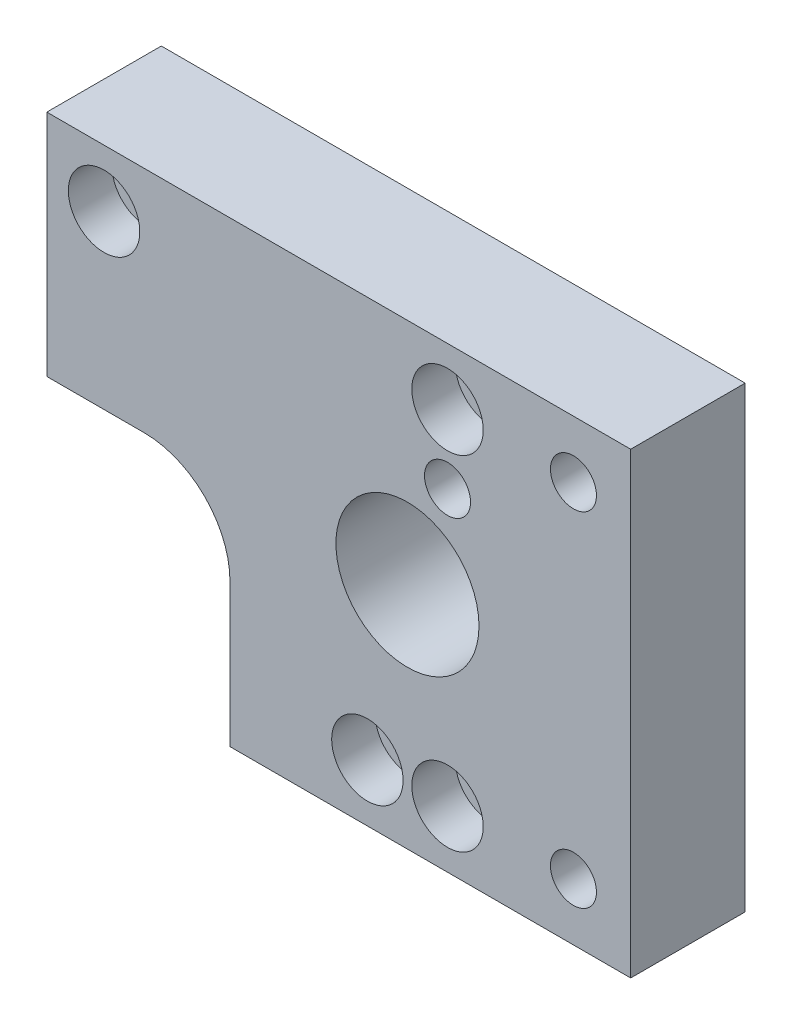
SolidWorks part; units mm, degrees
material "1060 Alloy"
ref_plane "Front Plane" through (0, 0, 0) normal (0, 0, 1) x (1, 0, 0)
ref_plane "Top Plane" through (0, 0, 0) normal (0, 1, 0) x (1, 0, 0)
ref_plane "Right Plane" through (0, 0, 0) normal (1, 0, 0) x (0, 0, -1)
sketch "Sketch1" plane through (0, 0, 0) normal (0, 0, 1) x (1, 0, 0)
  line L0 (0, 25.4) -> (0, 0) construction
  line L1 (-25.4, -25.4) -> (39.37, -25.4)
  line L2 (-25.4, -25.4) -> (-25.4, 25.4)
  line L3 (-25.4, 25.4) -> (39.37, 25.4)
  line L4 (39.37, -25.4) -> (39.37, 25.4)
  line L7 (39.37, 0) -> (-25.4, 0) construction
  circle A0 centre (-19.05, 19.05) radius 2.5527
  circle A1 centre (19.05, 19.05) radius 2.5527
  circle A2 centre (19.05, -19.05) radius 2.5527
  circle A3 centre (10.16, -19.05) radius 2.5527
  circle A4 centre (14.605, 0) radius 7.9375
  point P0 (0, 0)
  dimension "D3" = 5.1054
  dimension "D7" = 15.875
  dimension "D1" = 64.77
  dimension "D2" = 50.8
  dimension "D4" = 38.1
  dimension "D5" = 6.35
  dimension "D6" = 4.445
  dimension "D8" = 38.1
  dimension "D9" = 8.89
  dimension "D10" = 25.4
extrude "Boss-Extrude1" add sketch "Sketch1" along normal blind 12.7
hole_wizard "#7 (0.201) Diameter Hole1" positions "Sketch4" profile "Sketch5" hole size "#7" standard "ANSI Inch"
sketch "Sketch4" plane through (-24.7212, -12.8643, 0) normal (0, 0, 1) x (1, 0, 0)
  line L0 (64.0912, -12.5357) -> (64.0912, 38.2643) construction
  line L2 (64.0912, 38.2643) -> (-0.6788, 38.2643) construction
  circle A5 centre (43.7712, -6.1857) radius 2.5527 construction
  circle A6 centre (43.7712, -6.1857) radius 2.5527 construction
  circle A7 centre (43.7712, 31.9143) radius 2.5527 construction
  circle A8 centre (43.7712, 31.9143) radius 2.5527 construction
  point P0 (57.7412, -6.1857)
  point P7 (57.7412, 31.9143)
  point P33 (43.7712, 24.2943)
  dimension "D3" = 7.62
  dimension "D1" = 6.35
  dimension "D2" = 6.35
sketch "Sketch5" plane through (33.02, -19.05, 0) normal (1, 0, 0) x (0, 1, 0)
  line L0 (0, 0) -> (0, 71.6378)
  line L1 (0, 71.6378) -> (2.5527, 70.104)
  line L2 (2.5527, 70.104) -> (2.5527, 0)
  line L5 (2.5527, 0) -> (0, 0)
  line L10 (0, 71.6378) -> (-2.5527, 70.104) construction
  line L11 (0, -6.35) -> (0, 107.95) construction
  dimension "Hole Dia." = 5.1054
  dimension "Hole Depth" = 70.104
  dimension "Drill Angle" = 118
sketch "Sketch6" plane through (0, 0, 12.7) normal (0, 0, -1) x (-1, 0, 0)
  circle A0 centre (-19.05, 19.05) radius 3.9624
  circle A3 centre (-19.05, -19.05) radius 3.9624
  circle A4 centre (-10.16, -19.05) radius 3.9624
  circle A5 centre (19.05, 19.05) radius 3.9624
  dimension "D1" = 7.9248
extrude "Cut-Extrude1" cut sketch "Sketch6" along normal blind 4.826
sketch "Sketch7" plane through (0, 0, 0) normal (0, 0, -1) x (-1, 0, 0)
  line L1 (25.4, -25.4) -> (5.08, -25.4)
  line L2 (25.4, -25.4) -> (25.4, 0)
  line L3 (25.4, 0) -> (5.08, 0)
  line L4 (5.08, -25.4) -> (5.08, 0)
  dimension "D1" = 20.32
extrude "Cut-Extrude2" cut sketch "Sketch7" against normal through all
fillet "Fillet2" radius 9.525 1 edges at (-5.08, 0, 6.35)
